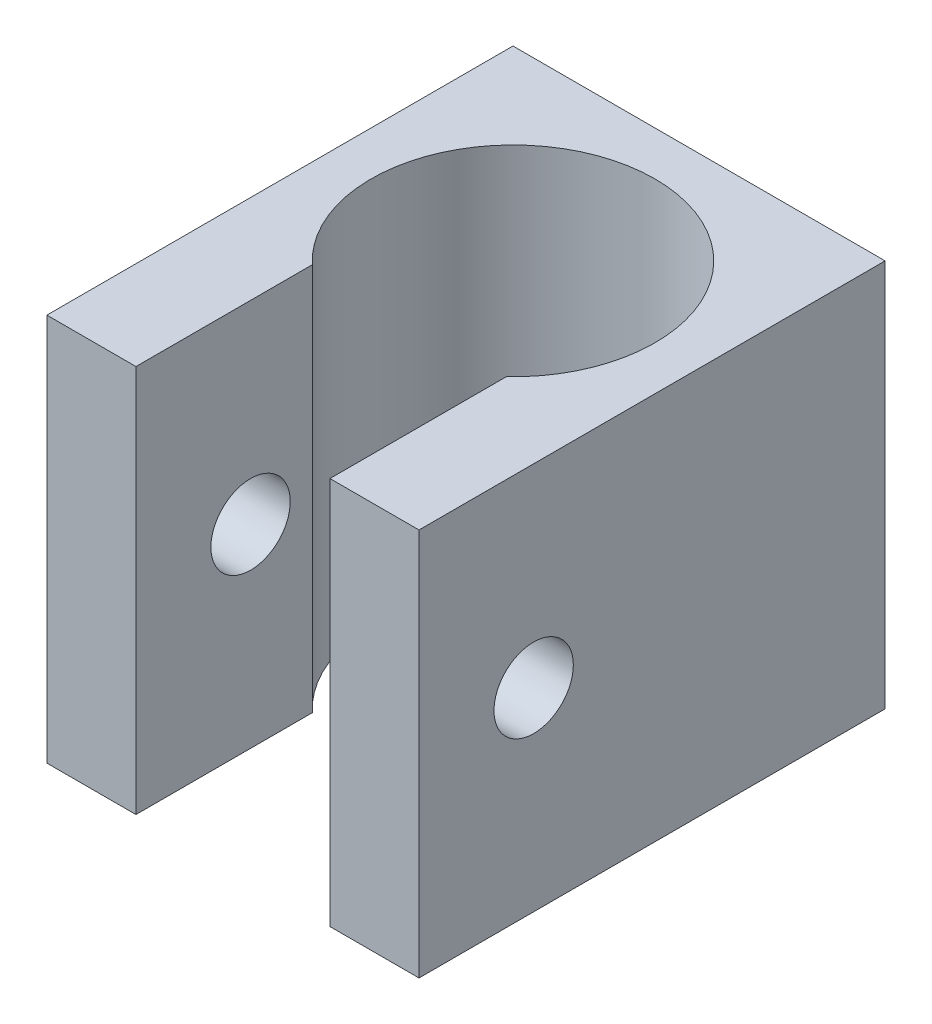
SolidWorks part; units mm, degrees
ref_plane "Front Plane" through (0, 0, 0) normal (0, 0, 1) x (1, 0, 0)
ref_plane "Top Plane" through (0, 0, 0) normal (0, 1, 0) x (1, 0, 0)
ref_plane "Right Plane" through (0, 0, 0) normal (1, 0, 0) x (0, 0, -1)
sketch "Sketch1" plane through (0, 0, 0) normal (0, 1, 0) x (1, 0, 0)
  line L0 (-5.5, -15) -> (-10.55, -15)
  line L1 (-10.55, -15) -> (-10.55, 11.4281)
  line L2 (-10.55, 11.4281) -> (10.55, 11.4281)
  line L3 (10.55, 11.4281) -> (10.55, -15)
  line L4 (10.55, -15) -> (5.5, -15)
  line L5 (5.5, -15) -> (5.5, -5)
  line L6 (-5.5, -15) -> (-5.5, -5)
  line L7 (-44.2539, 0) -> (44.2539, 0) construction
  line L8 (0, -44.7868) -> (0, 44.7868) construction
  arc A0 (-5.5, -5) -> (5.5, -5) centre (0, 0.8781) cw
  dimension "D1" = 8.05
  dimension "D2" = 11
  dimension "D3" = 10
  dimension "D4" = 10
  dimension "D5" = 21.1
  dimension "D6" = 10.55
  dimension "D7" = 15
  dimension "D8" = 10.55
extrude "Boss-Extrude1" add sketch "Sketch1" along normal mid plane 22
sketch "Sketch2" plane through (10.55, 0, 0) normal (1, 0, 0) x (0, 0, -1)
  line L0 (55, 0) -> (-55, 0) construction
  line L1 (-15, 11) -> (-15, -11) construction
  circle A0 centre (-8.5, 0) radius 2.25
  dimension "D1" = 6.5
  dimension "D2" = 4.5
extrude "Cut-Extrude1" cut sketch "Sketch2" against normal up to surface (21.1 mm away) up to face at (-10.55, 0, 1.7859)
equation "\"Width\"=21.1"
equation "\"D5@Sketch1\"=\"Width\""
equation "\"D8@Sketch1\"=\"Width\"/2"
equation "\"D6@Sketch1\"=\"Width\"/2"
